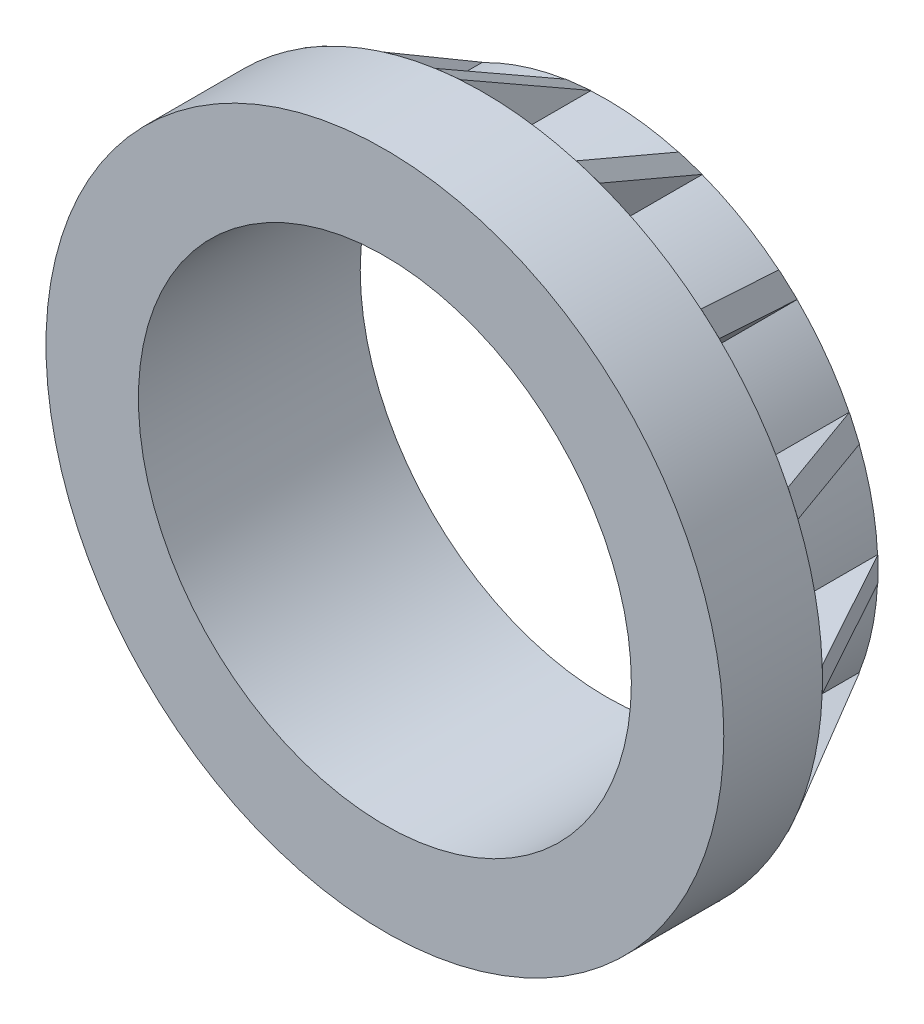
SolidWorks part; units mm, degrees
ref_plane "Ön Düzlem" through (0, 0, 0) normal (0, 0, 1) x (1, 0, 0)
ref_plane "Üst Düzlem" through (0, 0, 0) normal (0, 1, 0) x (1, 0, 0)
ref_plane "Sağ Düzlem" through (0, 0, 0) normal (1, 0, 0) x (0, 0, -1)
sketch "Sketch1" plane through (0, 0, 0) normal (0, 0, 1) x (1, 0, 0)
  circle A0 centre (0, 0) radius 27.5
  circle A1 centre (0, 0) radius 20
  dimension "D1" = 40
  dimension "D2" = 55
extrude "Boss-Extrude1" add sketch "Sketch1" against normal blind 8
sketch "Sketch2" plane through (0, 0, -8) normal (0, 0, -1) x (-1, 0, 0)
  circle A0 centre (0, 0) radius 22
  circle A1 centre (0, 0) radius 20 construction
  circle A2 centre (0, 0) radius 20
  dimension "D1" = 44
extrude "Boss-Extrude2" add sketch "Sketch2" along normal blind 10
sketch "Sketch3" plane through (0, 0, 0) normal (0, 1, 0) x (1, 0, 0)
  line L0 (22, 18) -> (27.5, 8)
  line L1 (22, 18) -> (20.5, 18)
  line L2 (22, 18) -> (-22, 18) construction
  line L3 (20.5, 18) -> (20.5, 8)
  line L4 (27.5, 8) -> (-27.5, 8) construction
  line L5 (20.5, 8) -> (27.5, 8)
  dimension "D1" = 1.5
extrude "Boss-Extrude3" add sketch "Sketch3" along normal mid plane 2 contours L0 L5 L3 L1
pattern_circular "CirPattern1" count 15 over 360 about axis through (0, 0, 0) along (0, 0, 1) of "Boss-Extrude3"
